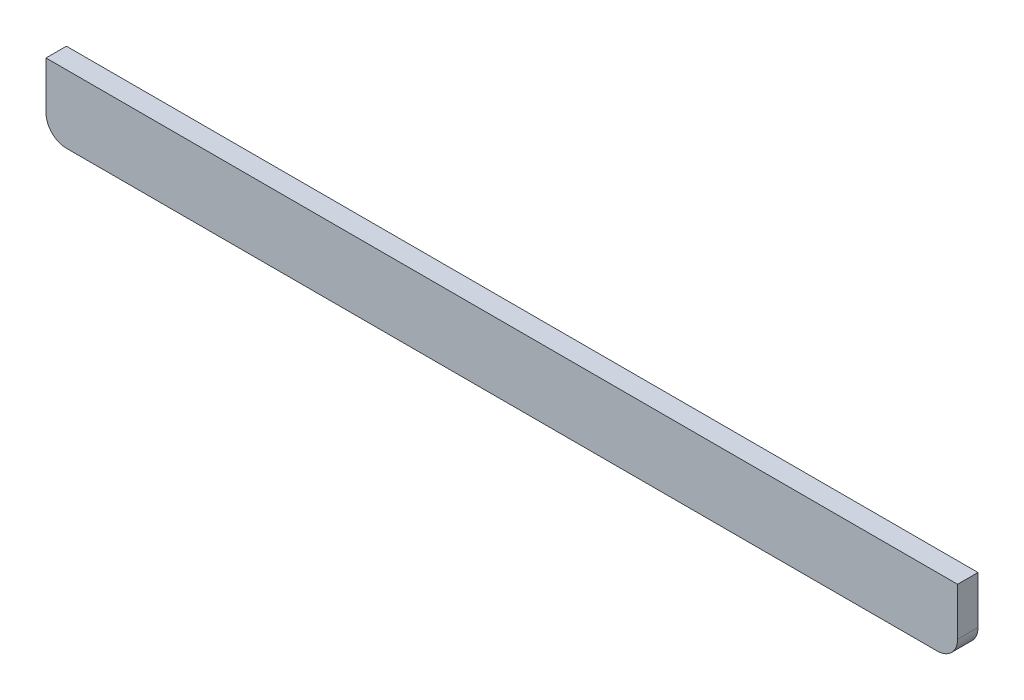
SolidWorks part; units mm, degrees
material "5052-H32"
ref_plane "Front Plane" through (0, 0, 0) normal (0, 0, 1) x (1, 0, 0)
ref_plane "Top Plane" through (0, 0, 0) normal (0, 1, 0) x (1, 0, 0)
ref_plane "Right Plane" through (0, 0, 0) normal (1, 0, 0) x (0, 0, -1)
sketch "Sketch2" plane through (0, 0, 0) normal (0, 0, 1) x (1, 0, 0)
  line L1 (0, 0) -> (134, 0)
  line L2 (0, 0) -> (0, 10)
  line L3 (0, 10) -> (134, 10)
  line L4 (134, 0) -> (134, 10)
  dimension "D1" = 134
  dimension "D2" = 10
extrude "Boss-Extrude1" add sketch "Sketch2" along normal blind 3 contours L3 L4 L1 L2
fillet "Fillet1" radius 3 2 edges at (134, 0, 1.5) (0, 0, 1.5)
sketch "Sketch3" plane through (0, 0, 3) normal (0, 0, 1) x (1, 0, 0)
  line L0 (131, 0) -> (3, 0)
  line L1 (131, 0) -> (3, 0)
  line L2 (0, 3) -> (0, 10)
  line L3 (0, 3) -> (0, 10)
  line L4 (0, 10) -> (134, 10)
  line L5 (0, 10) -> (134, 10)
  line L6 (134, 10) -> (134, 3)
  line L7 (134, 10) -> (134, 3)
  arc A0 (131, 0) -> (134, 3) centre (131, 3) ccw
  arc A1 (131, 0) -> (134, 3) centre (131, 3) ccw
  arc A2 (0, 3) -> (3, 0) centre (3, 3) ccw
  arc A3 (0, 3) -> (3, 0) centre (3, 3) ccw
